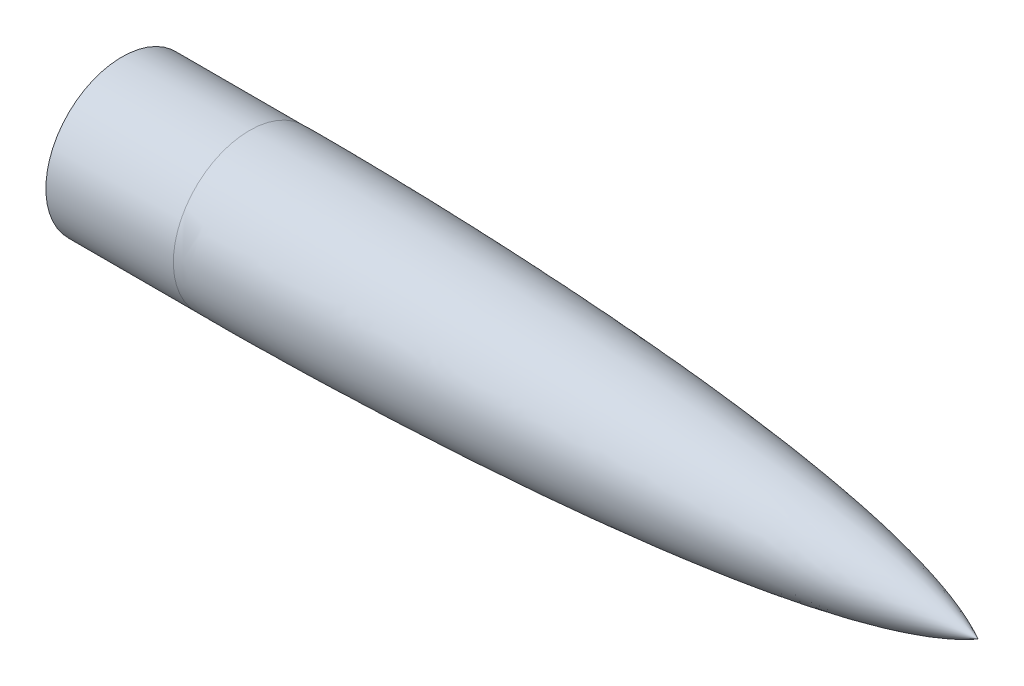
SolidWorks part; units mm, degrees
ref_plane "Front Plane" through (0, 0, 0) normal (0, 0, 1) x (1, 0, 0)
ref_plane "Top Plane" through (0, 0, 0) normal (0, 1, 0) x (1, 0, 0)
ref_plane "Right Plane" through (0, 0, 0) normal (1, 0, 0) x (0, 0, -1)
sketch "Sketch3" plane through (0, 0, 0) normal (0, 0, 1) x (1, 0, 0)
  line L0 (0, 0) -> (0, 20.8999) construction
  line L1 (0, 20.8999) -> (0, -93.2509) construction
  line L2 (0, 0) -> (200, 0) construction
  line L3 (200, 0) -> (192.7317, 0)
  line L7 (200, 0) -> (0, 0) construction
  line L8 (0, 0) -> (-147.4063, 0) construction
  line L9 (0, 20.8999) -> (-35, 20.8999)
  line L10 (-35, 20.8999) -> (-35, 19.3)
  line L11 (-35, 19.3) -> (0, 19.3)
  line L12 (0, 19.3) -> (41.7788, 17.3778)
  line L13 (200, 0) -> (198.5, 0) construction
  line L18 (147.7296, 9.8948) -> (178.1373, 3.3836)
  line L20 (188.7489, 0) -> (192.7317, 0)
  line L22 (185.555, 0) -> (188.7489, 0)
  line L24 (188.7489, 0.3697) -> (188.7489, 0.3697) construction
  line L25 (45.6216, 16.2674) -> (45.6216, 16.2674) construction
  line L26 (45.6216, 16.2674) -> (45.6216, 16.2674) construction
  line L27 (45.6216, 16.2674) -> (45.6216, 16.2674) construction
  line L28 (45.6216, 16.2674) -> (45.6216, 16.2674) construction
  arc A0 (185.555, 0) -> (184.2659, 1.7607) centre (183.708, 0) ccw
  spline S0 degree 3 poles (0, 20.8999) (23.6648, 21.1638) (163.1776, 19.7644) (200, 0) knots 0 0 0 0 1 1 1 1
  spline S1 degree 1 poles (0.0335, 17.9001) (198.5812, -2.6433) knots 0 0 1 1 construction
  spline S2 degree 3 poles (0.0335, 17.9001) (0.2235, 17.9022) (0.5934, 17.906) (1.4154, 17.9129) (2.5379, 17.9198) (4.0496, 17.9249) (6.2709, 17.927) (9.4236, 17.9197) (13.7662, 17.8921) (18.6279, 17.8425) (25.5528, 17.7458) (32.3036, 17.6157) (39.544, 17.44) (44.2311, 17.3119) (52.5432, 17.0557) (63.715, 16.6478) (79.0456, 15.9317) (94.8448, 15.006) (110.7908, 13.8466) (126.0944, 12.4717) (137.1113, 11.2575) (145.3231, 10.2273) (150.5847, 9.5104) (159.2026, 8.2181) (167.3462, 6.7927) (175.4572, 5.072) (181.1235, 3.6952) (186.328, 2.2321) (190.2417, 0.9424) (193.0936, -0.1287) (195.0874, -0.9508) (196.6195, -1.6486) (197.7706, -2.2165) (198.3097, -2.4976) (198.5812, -2.6433) knots 0 0 0 0 0.007812 0.015625 0.03125 0.046875 0.0625 0.09375 0.125 0.15625 0.1875 0.246564 0.262189 0.293439 0.3125 0.375 0.4375 0.5 0.5625 0.625 0.681957 0.697582 0.728832 0.75 0.8125 0.84375 0.875 0.90625 0.9375 0.953125 0.96875 0.984375 0.992188 1 1 1 1 only from (41.7788, 17.3778) to (147.7296, 9.8948)
  spline S3 degree 1 poles (45.6216, 16.2674) (188.7489, 0.3697) knots 0 0 1 1 construction
  spline S4 degree 3 poles (45.6216, 16.2674) (47.0733, 16.2241) (49.9497, 16.1343) (55.9166, 15.9314) (63.5971, 15.6365) (73.1372, 15.2092) (86.1647, 14.5341) (102.8329, 13.4773) (122.804, 11.8211) (138.8833, 10.0788) (151.0823, 8.4457) (159.8165, 7.0964) (168.0519, 5.6182) (173.7367, 4.4217) (177.3047, 3.5874) (178.7284, 3.2403) (180.5112, 2.7908) (182.1357, 2.3614) (183.7045, 1.9228) (184.7696, 1.6156) (185.9163, 1.2751) (187.2894, 0.8496) (188.2596, 0.5334) (188.7489, 0.3697) knots 0.295744 0.295744 0.295744 0.295744 0.315397 0.335049 0.374355 0.413661 0.452967 0.531578 0.61019 0.688801 0.728107 0.767413 0.806719 0.846025 0.855026 0.864852 0.869766 0.88533 0.893241 0.898154 0.904983 0.91481 0.924636 0.924636 0.924636 0.924636 only from (178.1373, 3.3836) to (184.2659, 1.7607)
  point P28 (198.7874, 0.626)
  dimension "D2" = 4
  dimension "D1" = 3
revolve "Revolve2" add sketch "Sketch3" angle 360 about L8
